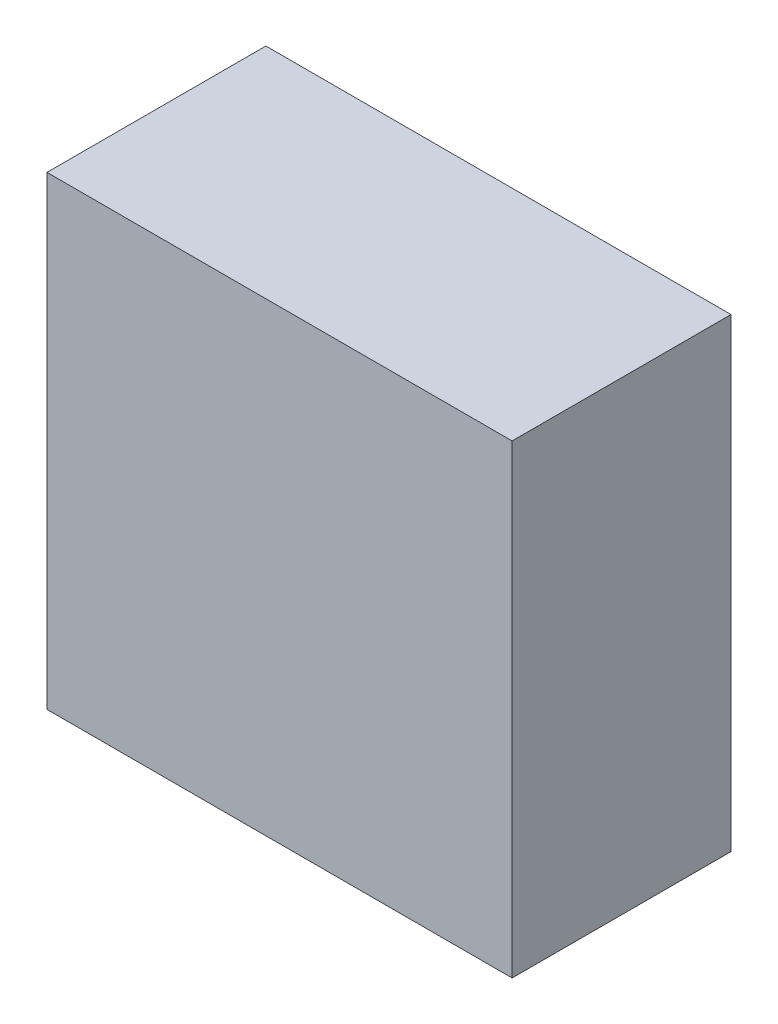
SolidWorks part; units mm, degrees
ref_plane "前视基准面" through (0, 0, 0) normal (0, 0, 1) x (1, 0, 0)
ref_plane "上视基准面" through (0, 0, 0) normal (0, 1, 0) x (1, 0, 0)
ref_plane "右视基准面" through (0, 0, 0) normal (1, 0, 0) x (0, 0, -1)
sketch "草图1" plane through (0, 0, 0) normal (0, 0, 1) x (1, 0, 0)
  line L0 (0, 0) -> (0, 50000) construction
  line L1 (0, 0) -> (50000, 0) construction
  line L3 (-17, 17) -> (17, 17)
  line L4 (-17, 17) -> (-17, -17)
  line L5 (-17, -17) -> (17, -17)
  line L6 (17, 17) -> (17, -17)
extrude "凸台-拉伸1" add sketch "草图1" along normal blind 16
sketch "草图3" plane through (0, 0, 0) normal (0, 0, -1) x (-1, 0, 0)
  line L0 (0, 0) -> (50000, 0) construction
  line L1 (0, 0) -> (0, 50000) construction
  circle A0 centre (0, 0) radius 1.5
extrude "切除-拉伸1" cut sketch "草图3" against normal blind 3
